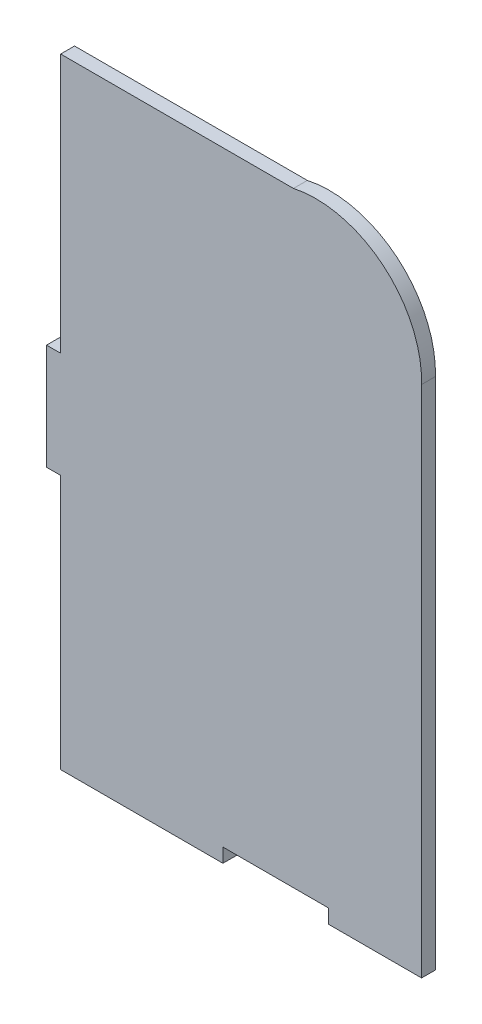
SolidWorks part; units mm, degrees
ref_plane "Front Plane" through (0, 0, 0) normal (0, 0, 1) x (1, 0, 0)
ref_plane "Top Plane" through (0, 0, 0) normal (0, 1, 0) x (1, 0, 0)
ref_plane "Right Plane" through (0, 0, 0) normal (1, 0, 0) x (0, 0, -1)
sketch "Sketch1" plane through (0, 0, 0) normal (0, 0, 1) x (1, 0, 0)
  line L0 (215.8361, -23.47) -> (383.5283, -23.47)
  line L1 (475.8296, -99.67) -> (475.8296, -469.9)
  line L2 (215.8361, -23.47) -> (215.8361, -210.16)
  line L6 (215.8361, -210.16) -> (205.6696, -210.16)
  line L8 (205.6696, -210.16) -> (205.6696, -286.36)
  line L10 (205.6696, -286.36) -> (215.8296, -286.36)
  line L12 (215.8296, -286.36) -> (215.8296, -469.9)
  line L13 (215.8296, -469.9) -> (332.7218, -469.9)
  line L14 (408.9218, -469.9) -> (408.9218, -459.74)
  line L15 (408.9218, -459.74) -> (332.7218, -459.74)
  line L16 (332.7218, -459.74) -> (332.7218, -469.9)
  line L17 (408.9218, -469.9) -> (475.8296, -469.9)
  arc A2 (475.8296, -99.67) -> (383.5283, -23.47) centre (399.6491, -97.9452) ccw
  dimension "D1" = 76.2
  dimension "D2" = 186.69
  dimension "D3" = 10.16
  dimension "D4" = 116.8922
  dimension "D5" = 260
extrude "Boss-Extrude1" add sketch "Sketch1" against normal blind 10
